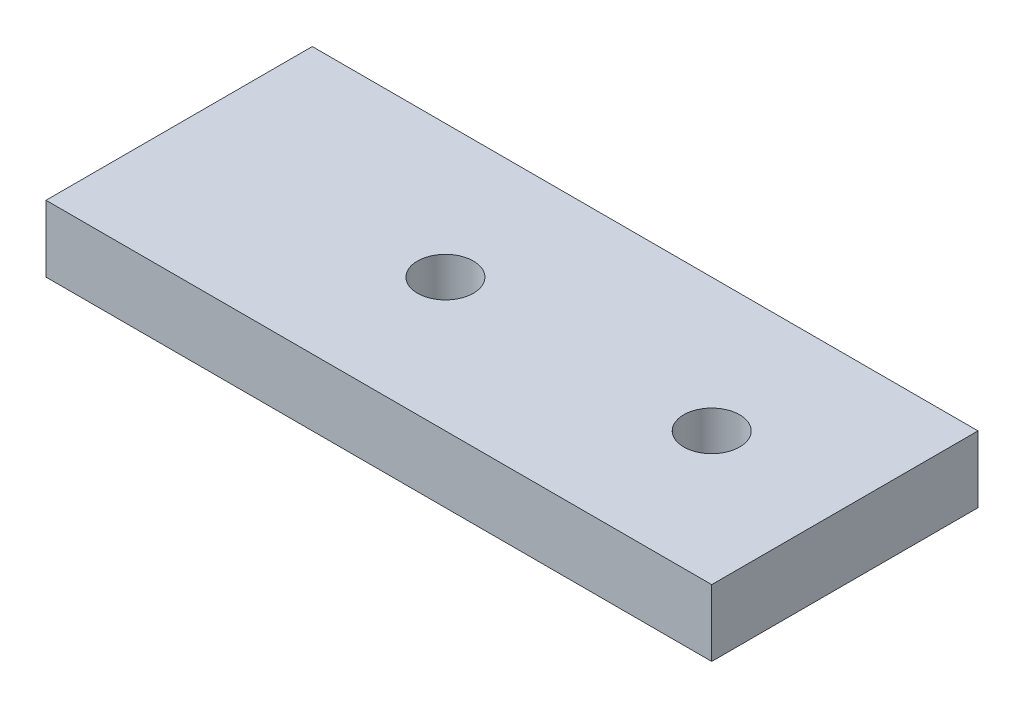
SolidWorks part; units mm, degrees
ref_plane "Front Plane" through (0, 0, 0) normal (0, 0, 1) x (1, 0, 0)
ref_plane "Top Plane" through (0, 0, 0) normal (0, 1, 0) x (1, 0, 0)
ref_plane "Right Plane" through (0, 0, 0) normal (1, 0, 0) x (0, 0, -1)
sketch "Sketch1" plane through (0, 0, 0) normal (0, 1, 0) x (1, 0, 0)
  line L1 (0, 0) -> (63.5, 0)
  line L2 (0, 0) -> (0, 25.4)
  line L3 (0, 25.4) -> (63.5, 25.4)
  line L4 (63.5, 0) -> (63.5, 25.4)
  dimension "D1" = 25.4
  dimension "D2" = 63.5
extrude "Boss-Extrude1" add sketch "Sketch1" along normal blind 6.35
sketch "Sketch2" plane through (0, 6.35, 0) normal (0, 1, 0) x (1, 0, 0)
  line L0 (0, 12.7) -> (56.0638, 12.7) construction
  line L1 (0, 25.4) -> (0, 0) construction
  line L2 (63.5, 0) -> (63.5, 25.4) construction
  circle A0 centre (25.4, 12.7) radius 2.667
  circle A1 centre (50.8, 12.7) radius 2.667
  dimension "D1" = 5.334
  dimension "D2" = 5.334
  dimension "D3" = 25.4
  dimension "D4" = 12.7
extrude "Cut-Extrude1" cut sketch "Sketch2" against normal through all
